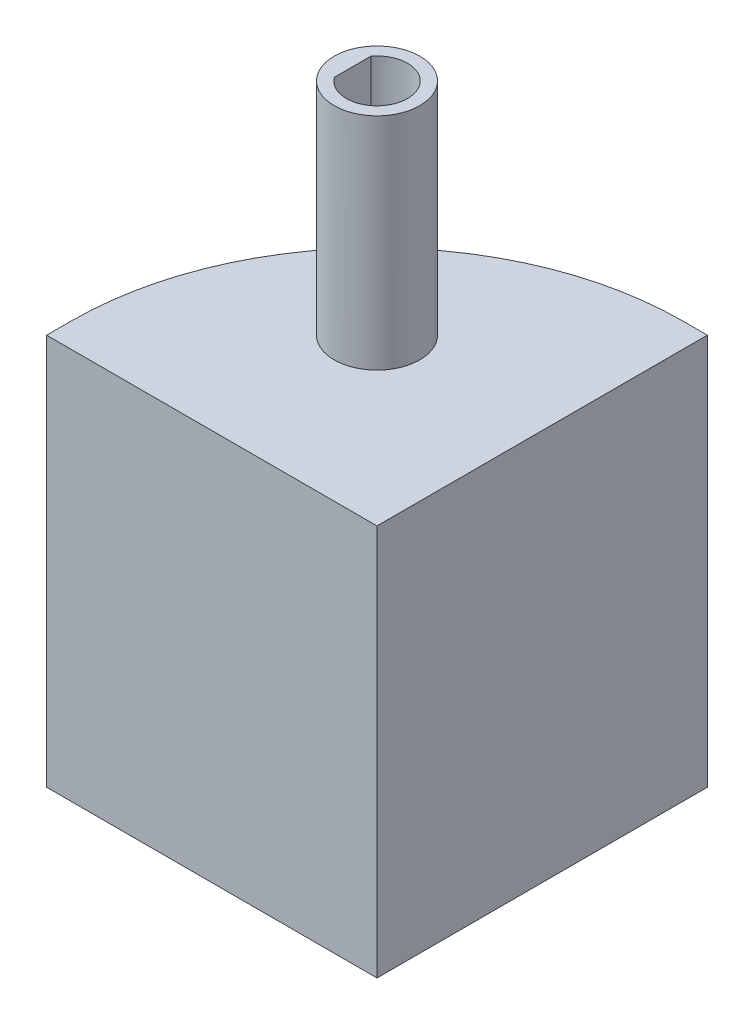
SolidWorks part; units mm, degrees
ref_plane "Front Plane" through (0, 0, 0) normal (0, 0, 1) x (1, 0, 0)
ref_plane "Top Plane" through (0, 0, 0) normal (0, 1, 0) x (1, 0, 0)
ref_plane "Right Plane" through (0, 0, 0) normal (1, 0, 0) x (0, 0, -1)
sketch "Sketch1" plane through (0, 0, 0) normal (0, 0, 1) x (1, 0, 0)
  line L0 (0, 0) -> (25, 0)
  dimension "D1" = 25
extrude "Extrude-Thin1" add sketch "Sketch1" against normal blind 25 thin thin type one direction reverse wall 2
sketch "Sketch2" plane through (0, 2, 0) normal (0, 1, 0) x (1, 0, 0)
  line L0 (0, 25) -> (25, 25) construction
  line L1 (0, 25) -> (0, 0) construction
  line L2 (12.5, 22.5) -> (12.5, 25)
  line L3 (0, 7.5) -> (3.8397, 7.5)
  line L5 (0, 0) -> (25, 0) construction
  line L7 (0, 25) -> (0, 0)
  line L8 (0, 25) -> (25, 25)
  circle A0 centre (12.5, 12.5) radius 6.0005
  arc A1 (12.5, 22.5) -> (3.8397, 7.5) centre (12.5, 12.5) ccw
  line M7 (25, 25) -> (0, 25)
  line M8 (0, 25) -> (0, 0)
  dimension "D1" = 12.001
  dimension "D2" = 12.5
  dimension "D3" = 12.5
  dimension "D4" = 20
  dimension "D6" = 7.5
extrude "Cut-Extrude1" cut sketch "Sketch2" against normal through all contours A1 L2 L3 M7 M8 | A0
sketch "Sketch4" plane through (0, 0, 0) normal (0, -1, 0) x (1, 0, 0)
  line L0 (0, 0) -> (0, 2)
  line L1 (0, 2) -> (27, 2)
  line L2 (27, 2) -> (27, -25)
  line L3 (27, -25) -> (25, -25)
  line L4 (0, 0) -> (25, 0) construction
  line L5 (0, 0) -> (25, 0)
  line L6 (25, -25) -> (25, 0) construction
  line L7 (25, -25) -> (25, 0)
  dimension "D1" = 2
  dimension "D2" = 2
extrude "Boss-Extrude1" add sketch "Sketch4" against normal blind 32
sketch "Sketch6" plane through (0, 32, 0) normal (0, 1, 0) x (1, 0, 0)
  line L0 (0, 0) -> (25, 0) construction
  line L1 (0, 0) -> (25, 0)
  line L2 (25, 0) -> (25, 25) construction
  line L3 (25, 0) -> (25, 25)
  arc A0 (0, 0) -> (25, 25) centre (25, 0) cw
  dimension "D1" = 25
extrude "Boss-Extrude2" add sketch "Sketch6" against normal blind 2
sketch "Sketch7" plane through (0, 32, 0) normal (0, 1, 0) x (1, 0, 0)
  line L0 (25, 25) -> (27, 25) construction
  line L1 (11.5, 13) -> (11.5, 10)
  arc A0 (11.5, 10) -> (11.5, 13) centre (13.5, 11.5) ccw
  circle A1 centre (13.5, 11.5) radius 3.5
  dimension "D1" = 5
  dimension "D3" = 13.5
  dimension "D4" = 7
  dimension "D2" = 13.5
  dimension "D5" = 3
extrude "Boss-Extrude3" add sketch "Sketch7" along normal blind 18
